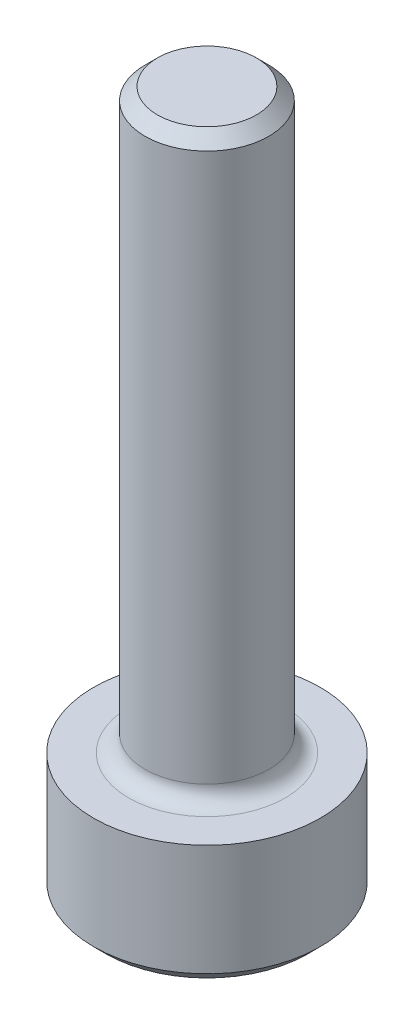
SolidWorks part; units mm, degrees
ref_plane "Front Plane" through (0, 0, 0) normal (0, 0, 1) x (1, 0, 0)
ref_plane "Top Plane" through (0, 0, 0) normal (0, 1, 0) x (1, 0, 0)
ref_plane "Right Plane" through (0, 0, 0) normal (1, 0, 0) x (0, 0, -1)
sketch "Sketch2" plane through (0, 0, 0) normal (0, 1, 0) x (1, 0, 0)
  circle A0 centre (0, 0) radius 1.5
extrude "Boss-Extrude1" add sketch "Sketch2" along normal blind 14
sketch "Sketch3" plane through (0, 0, 0) normal (0, 1, 0) x (1, 0, 0)
  circle A0 centre (0, 0) radius 2.75
  dimension "D1" = 5.5
extrude "Boss-Extrude2" add sketch "Sketch3" against normal blind 3
fillet "Fillet1" radius 0.4 1 edges at (0, 0, 1.5)
chamfer "Chamfer1" distance 0.3 angle 45 2 edges at (0, 14, 1.5) (0, -3, 2.75)
sketch "Sketch4" plane through (0, -3, 0) normal (0, -1, 0) x (1, 0, 0)
  line L1 (0, 1.4434) -> (-1.25, 0.7217)
  line L2 (-1.25, 0.7217) -> (-1.25, -0.7217)
  line L3 (-1.25, -0.7217) -> (0, -1.4434)
  line L4 (0, -1.4434) -> (1.25, -0.7217)
  line L5 (1.25, -0.7217) -> (1.25, 0.7217)
  line L6 (1.25, 0.7217) -> (0, 1.4434)
  circle A0 centre (0, 0) radius 1.25 construction
  dimension "D1" = 2.5
extrude "Cut-Extrude1" cut sketch "Sketch4" against normal blind 2.5
